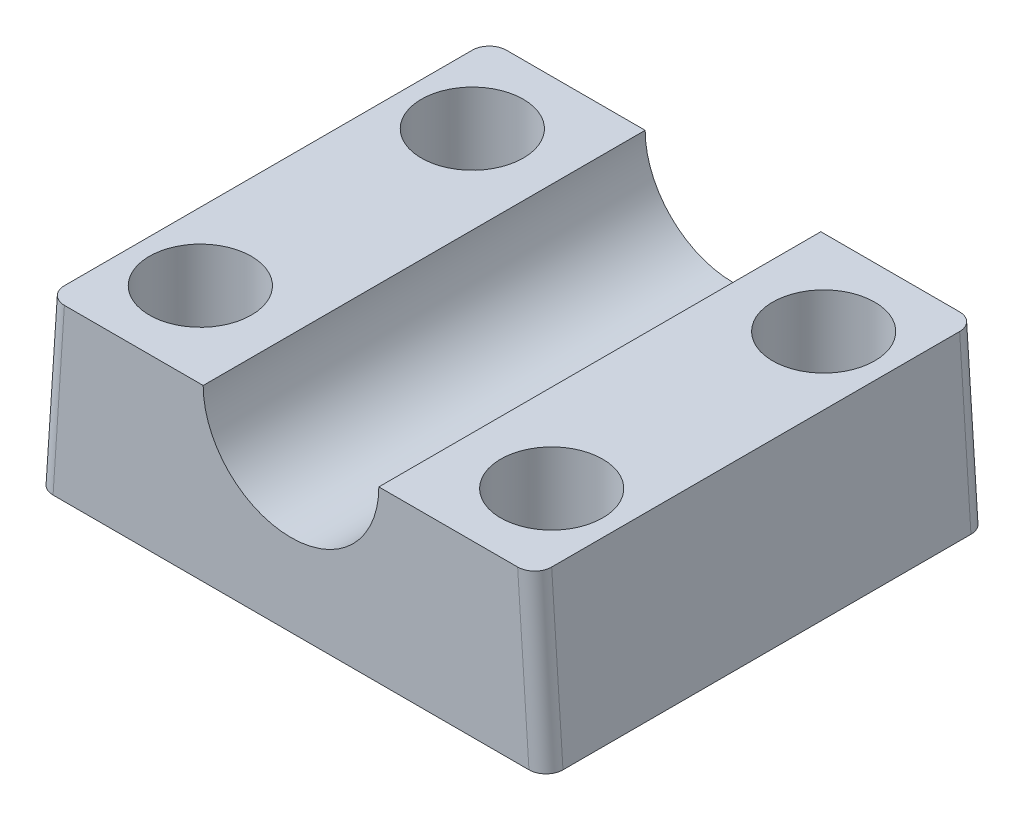
SolidWorks part; units mm, degrees
material "ABS"
ref_plane "Piano frontale" through (0, 0, 0) normal (0, 0, 1) x (1, 0, 0)
ref_plane "Piano superiore" through (0, 0, 0) normal (0, 1, 0) x (1, 0, 0)
ref_plane "Piano destro" through (0, 0, 0) normal (1, 0, 0) x (0, 0, -1)
sketch "Schizzo1" plane through (0, 0, 0) normal (0, 0, 1) x (1, 0, 0)
  line L0 (-7.75, 15) -> (-21.5, 15)
  line L1 (-21.5, 15) -> (-22.5, 0)
  line L2 (-22.5, 0) -> (22.5, 0)
  line L3 (22.5, 0) -> (21.5, 15)
  line L4 (21.5, 15) -> (7.75, 15)
  line L5 (0, 15) -> (0, 0) construction
  arc A0 (-7.75, 15) -> (7.75, 15) centre (0, 15) ccw
  dimension "D1" = 15.5
  dimension "D2" = 45
  dimension "D3" = 15
  dimension "D4" = 43
extrude "Estrusione-Estrusione1" add sketch "Schizzo1" along normal blind 39
sketch "Schizzo3" plane through (0, 0, 0) normal (0, -1, 0) x (-1, 0, 0)
  line L0 (-15.5, -7.5) -> (-15.5, -31.5) construction
  line L1 (-15.5, -31.5) -> (15.5, -31.5) construction
  line L2 (15.5, -31.5) -> (15.5, -7.5) construction
  line L3 (15.5, -7.5) -> (-15.5, -7.5) construction
  line L5 (22.5, 0) -> (-22.5, 0) construction
  point P0 (-15.5, -7.5)
  point P2 (15.5, -7.5)
  point P4 (15.5, -31.5)
  point P6 (-15.5, -31.5)
  dimension "D1" = 31
  dimension "D2" = 24
  dimension "D3" = 7.5
  dimension "D4" = 15.5
hole_wizard "Foro per Vite M8-1" positions "Schizzo3" profile "Schizzo4" hole size "M8" standard "ISO"
sketch "Schizzo4" plane through (15.5, 0, 7.5) normal (1, 0, 0) x (0, 0, -1)
  line L0 (0, 0) -> (0, 32.7039)
  line L1 (0, 32.7039) -> (4.5, 30)
  line L2 (4.5, 30) -> (4.5, 0)
  line L5 (4.5, 0) -> (0, 0)
  line L10 (0, 32.7039) -> (-4.5, 30) construction
  line L11 (0, -6.35) -> (0, 107.95) construction
  dimension "Hole Dia." = 9
  dimension "Hole Depth" = 30
  dimension "Drill Angle" = 118
fillet "Raccordo1" radius 1.5 4 edges at (22, 7.5, 39) (-22, 7.5, 39) (-22, 7.5, 0) (22, 7.5, 0)
